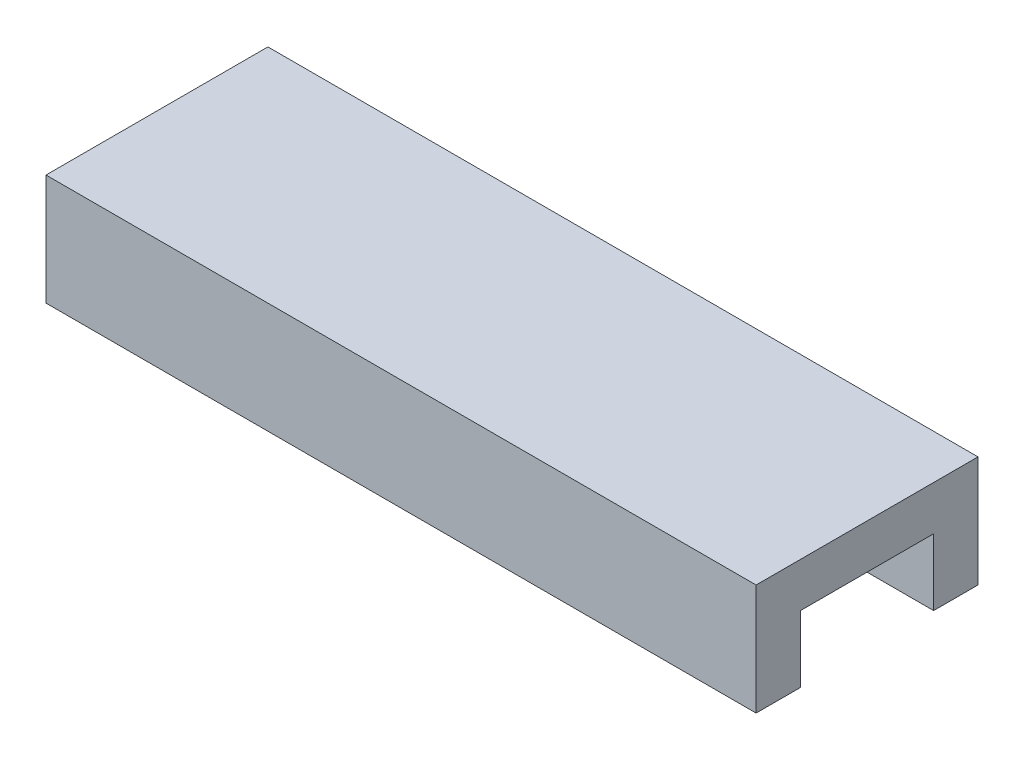
SolidWorks part; units mm, degrees
ref_plane "Front Plane" through (0, 0, 0) normal (0, 0, 1) x (1, 0, 0)
ref_plane "Top Plane" through (0, 0, 0) normal (0, 1, 0) x (1, 0, 0)
ref_plane "Right Plane" through (0, 0, 0) normal (1, 0, 0) x (0, 0, -1)
sketch "Sketch1" plane through (0, 0, 0) normal (1, 0, 0) x (0, 0, -1)
  line L0 (-19.9282, 0) -> (-19.9282, 25)
  line L1 (-19.9282, 25) -> (30.0718, 25)
  line L2 (30.0718, 25) -> (30.0718, 0)
  line L3 (30.0718, 0) -> (20.0718, 0)
  line L4 (20.0718, 0) -> (20.0718, 15)
  line L5 (20.0718, 15) -> (-9.9282, 15)
  line L6 (-9.9282, 15) -> (-9.9282, 0)
  line L7 (-9.9282, 0) -> (-19.9282, 0)
  dimension "D1" = 30
  dimension "D2" = 50
  dimension "D3" = 10
  dimension "D4" = 15
  dimension "D5" = 25
  dimension "D6" = 25
  dimension "D7" = 15
  dimension "D8" = 10
extrude "Extrude1" add sketch "Sketch1" along normal blind 160
